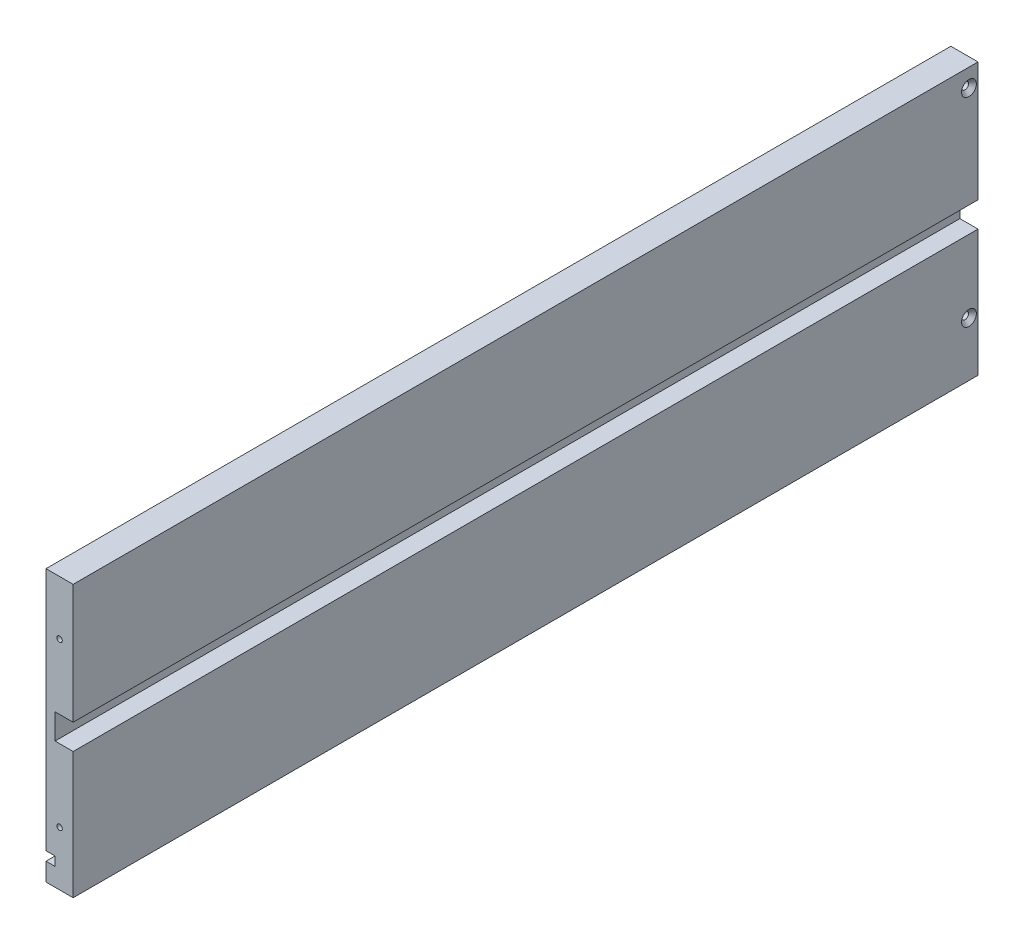
SolidWorks part; units mm, degrees
ref_plane "Front" through (0, 0, 0) normal (0, 0, 1) x (1, 0, 0)
ref_plane "Top" through (0, 0, 0) normal (0, 1, 0) x (1, 0, 0)
ref_plane "Right" through (0, 0, 0) normal (1, 0, 0) x (0, 0, -1)
sketch "Sketch2" plane through (0, 0, 0) normal (1, 0, 0) x (0, 0, -1)
  line L1 (0, 0) -> (500, 0)
  line L2 (0, 0) -> (0, 150)
  line L3 (0, 150) -> (500, 150)
  line L4 (500, 0) -> (500, 150)
  dimension "D1" = 500
  dimension "D2" = 150
extrude "Base-Extrude" add sketch "Sketch2" against normal blind 15
sketch "Sketch3" plane through (0, 0, 0) normal (0, 0, 1) x (1, 0, 0)
  line L0 (0, 150) -> (0, 0) construction
  line L1 (0, 70) -> (-10, 70)
  line L2 (0, 70) -> (0, 84)
  line L3 (0, 84) -> (-10, 84)
  line L4 (-10, 70) -> (-10, 84)
  line L5 (-15, 0) -> (0, 0) construction
  dimension "D1" = 70
  dimension "D2" = 10
  dimension "D3" = 14
extrude "Cut-Extrude1" cut sketch "Sketch3" against normal through all
sketch "Sketch4" plane through (0, 0, 0) normal (0, 0, 1) x (1, 0, 0)
  line L0 (-15, 150) -> (-15, 0) construction
  line L1 (-15, 10) -> (-10, 10)
  line L2 (-15, 10) -> (-15, 15)
  line L3 (-15, 15) -> (-10, 15)
  line L4 (-10, 10) -> (-10, 15)
  line L5 (-15, 0) -> (0, 0) construction
  dimension "D1" = 10
  dimension "D2" = 5
  dimension "D3" = 5
extrude "Cut-Extrude2" cut sketch "Sketch4" against normal through all
hole_wizard "CSK for M3.5 Flat Head Machine Screw1" positions "Sketch7" profile "Sketch6" countersink size "M3.5" standard "Ansi Metric" end condition through all
sketch "Sketch7" plane through (0, 0, 0) normal (1, 0, 0) x (0, 0, -1)
  line L0 (500, 84) -> (500, 150) construction
  line L1 (500, 150) -> (0, 150) construction
  line L2 (0, 0) -> (500, 0) construction
  point P0 (495, 140)
  point P5 (495, 30)
  dimension "D1" = 5
  dimension "D2" = 10
  dimension "D3" = 30
sketch "Sketch6" plane through (0, 140, -495) normal (0, 1, 0) x (0, 0, -1)
  line L0 (0, 0) -> (0, 15)
  line L1 (0, 15) -> (1.95, 15)
  line L2 (1.95, 15) -> (1.95, 2.15)
  line L3 (1.95, 2.15) -> (4.1, 0)
  line L5 (4.1, 0) -> (0, 0)
  line L6 (-1.95, 2.15) -> (-4.1, 0) construction
  line L11 (0, -6.35) -> (0, 107.95) construction
  dimension "Thru Hole Dia." = 3.9
  dimension "Thru Hole Depth" = 15
  dimension "Near C'Sink Dia." = 8.2
  dimension "Near C'Sink Angle" = 90
hole_wizard "M3.0 (3.000000) Diameter Hole1" positions "Sketch10" profile "Sketch9" hole size "M3.0" standard "Ansi Metric"
sketch "Sketch10" plane through (0, 0, 0) normal (0, 0, 1) x (1, 0, 0)
  line L0 (-7.5, 150) -> (-7.5, 0) construction
  line L1 (-15, 150) -> (0, 150) construction
  line L2 (-15, 0) -> (0, 0) construction
  point P0 (-7.5, 30)
  point P5 (-7.5, 120)
  dimension "D1" = 30
  dimension "D2" = 30
sketch "Sketch9" plane through (-7.5, 30, 0) normal (1, 0, 0) x (0, -1, 0)
  line L0 (0, 0) -> (0, 10.9013)
  line L1 (0, 10.9013) -> (1.5, 10)
  line L2 (1.5, 10) -> (1.5, 0)
  line L5 (1.5, 0) -> (0, 0)
  line L10 (0, 10.9013) -> (-1.5, 10) construction
  line L11 (0, -6.35) -> (0, 107.95) construction
  dimension "Hole Dia." = 3
  dimension "Hole Depth" = 10
  dimension "Drill Angle" = 118
